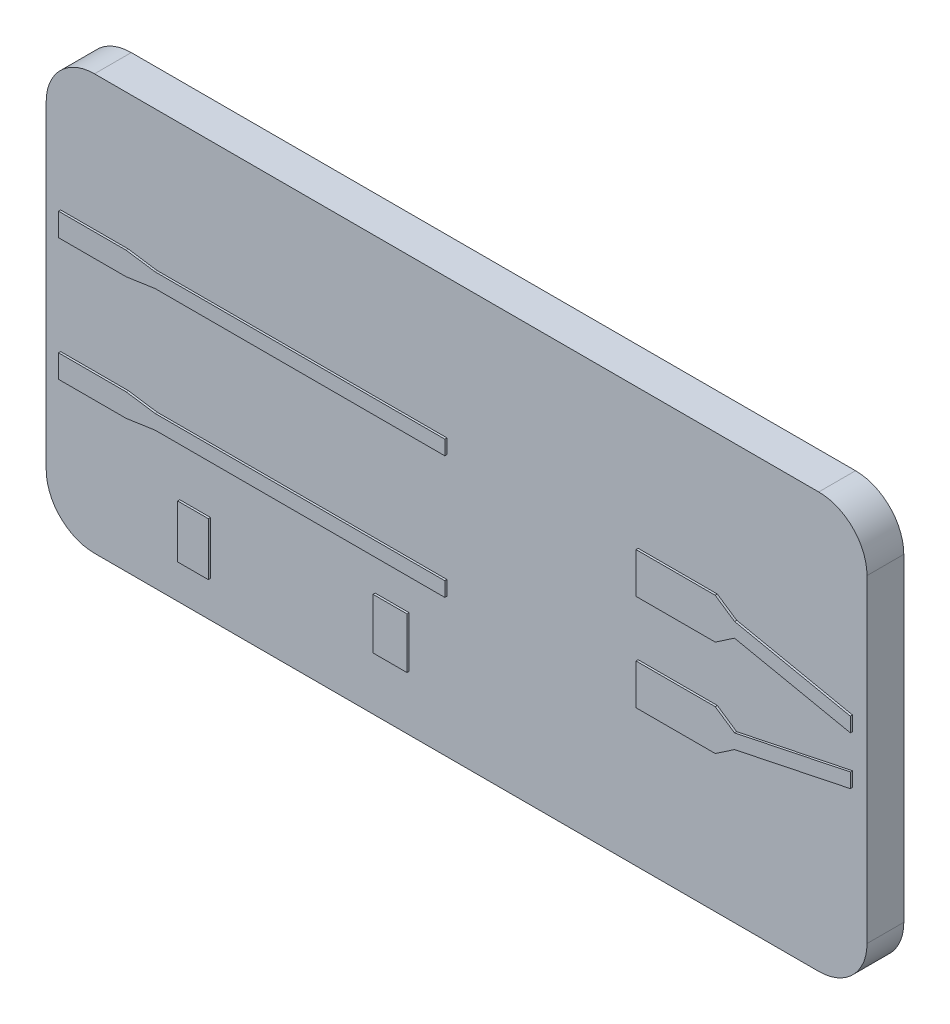
SolidWorks part; units mm, degrees
ref_plane "PL-01 Front" through (0, 0, 0) normal (0, 0, 1) x (1, 0, 0)
ref_plane "PL-02 Top" through (0, 0, 0) normal (0, 1, 0) x (1, 0, 0)
ref_plane "PL-03 Right" through (0, 0, 0) normal (1, 0, 0) x (0, 0, -1)
sketch "Sketch1" plane through (0, 0, 0) normal (0, 0, 1) x (1, 0, 0)
  line L1 (-8, 2.15) -> (-0.5, 2.15)
  line L2 (-8.5, 1.65) -> (-8.5, -1.65)
  line L3 (-8, -2.15) -> (-0.5, -2.15)
  line L4 (0, 1.65) -> (0, -1.65)
  arc A0 (-8.5, -1.65) -> (-8, -2.15) centre (-8, -1.65) ccw
  arc A1 (-8, 2.15) -> (-8.5, 1.65) centre (-8, 1.65) ccw
  arc A2 (-0.5, 2.15) -> (0, 1.65) centre (-0.5, 1.65) cw
  arc A3 (-0.5, -2.15) -> (0, -1.65) centre (-0.5, -1.65) ccw
  dimension "D1" = 0.5
  dimension "D2" = 4.3
  dimension "D3" = 8.5
extrude "BE-00 Board" add sketch "Sketch1" along normal blind 0.381
sketch "Sketch2" plane through (0, 0, 0.381) normal (0, 0, 1) x (1, 0, 0)
  line L0 (-0.15, -0.1751) -> (-0.15, -0.3249)
  line L1 (-0.15, -0.3249) -> (-1.35, -0.5745)
  line L2 (-1.35, -0.5745) -> (-1.5502, -0.7096)
  line L3 (-1.5502, -0.7096) -> (-2.37, -0.7096)
  line L4 (-2.37, -0.7096) -> (-2.37, -0.2896)
  line L5 (-2.37, -0.2896) -> (-1.5502, -0.2896)
  line L6 (-1.5502, -0.2896) -> (-1.35, -0.4246)
  line L7 (-1.35, -0.4246) -> (-0.15, -0.1751)
  line L8 (-1.35, -0.4246) -> (-1.35, -0.5745) construction
  line L9 (-1.0961, 0) -> (-2.5351, 0) construction
  line L10 (-4.35, -0.56) -> (-7.35, -0.56)
  line L11 (-7.35, -0.56) -> (-7.65, -0.516)
  line L12 (-7.65, -0.516) -> (-8.35, -0.516)
  line L13 (-8.35, -0.516) -> (-8.35, -0.754)
  line L14 (-8.35, -0.754) -> (-7.65, -0.754)
  line L15 (-7.65, -0.754) -> (-7.35, -0.71)
  line L16 (-7.35, -0.71) -> (-4.35, -0.71)
  line L17 (-4.35, -0.71) -> (-4.35, -0.56)
  line L19 (-8.5, 1.65) -> (-8.5, -1.65) construction
  line L20 (-4.35, 0.71) -> (-4.35, 0.56)
  line L21 (-7.35, 0.71) -> (-4.35, 0.71)
  line L22 (-7.65, 0.754) -> (-7.35, 0.71)
  line L23 (-8.35, 0.754) -> (-7.65, 0.754)
  line L24 (-8.35, 0.516) -> (-8.35, 0.754)
  line L25 (-7.65, 0.516) -> (-8.35, 0.516)
  line L26 (-7.35, 0.56) -> (-7.65, 0.516)
  line L27 (-4.35, 0.56) -> (-7.35, 0.56)
  line L28 (-1.35, 0.4246) -> (-0.15, 0.1751)
  line L29 (-1.5502, 0.2896) -> (-1.35, 0.4246)
  line L30 (-2.37, 0.2896) -> (-1.5502, 0.2896)
  line L31 (-2.37, 0.7096) -> (-2.37, 0.2896)
  line L32 (-1.5502, 0.7096) -> (-2.37, 0.7096)
  line L33 (-1.35, 0.5745) -> (-1.5502, 0.7096)
  line L34 (-0.15, 0.3249) -> (-1.35, 0.5745)
  line L35 (-0.15, 0.1751) -> (-0.15, 0.3249)
  line L36 (-7.1169, -1.228) -> (-6.7987, -1.228)
  line L37 (-7.1169, -1.228) -> (-7.1169, -1.775)
  line L38 (-7.1169, -1.775) -> (-6.7987, -1.775)
  line L39 (-6.7987, -1.228) -> (-6.7987, -1.775)
  line L40 (-5.0935, -1.0536) -> (-4.7413, -1.0536)
  line L41 (-5.0935, -1.0536) -> (-5.0935, -1.5796)
  line L42 (-5.0935, -1.5796) -> (-4.7413, -1.5796)
  line L43 (-4.7413, -1.0536) -> (-4.7413, -1.5796)
  point P11 (-1.35, -0.4996)
  point P12 (-2.37, -0.4996)
  point P23 (-8.35, -0.635)
  point P42 (-0.15, -0.25)
  dimension "D1" = 0.3501
  dimension "D2" = 0.1499
  dimension "D3" = 34
  dimension "D4" = 0.5791
  dimension "D5" = 0.15
  dimension "D6" = 1.35
  dimension "D7" = 2.37
  dimension "D8" = 0.635
  dimension "D9" = 0.42
  dimension "D10" = 0.238
  dimension "D11" = 0.15
  dimension "D12" = 0.7
  dimension "D13" = 3
  dimension "D14" = 0.8198
  dimension "D15" = 0.5
  dimension "D16" = 0.15
  dimension "D17" = 0.3
extrude "BE-00 Traces" add sketch "Sketch2" along normal blind 0.022
sketch "Sketch4" plane through (0, 0, 0) normal (0, 0, -1) x (-1, 0, 0)
  line L22 (0.5, -2.05) -> (8, -2.05)
  line L23 (0.1, 1.65) -> (0.1, -1.65)
  line L24 (8, 2.05) -> (0.5, 2.05)
  line L25 (8.4, -1.65) -> (8.4, 1.65)
  line L26 (0.5, -2.05) -> (8, -2.05)
  line L27 (0.1, 1.65) -> (0.1, -1.65)
  line L28 (8, 2.05) -> (0.5, 2.05)
  line L29 (8.4, -1.65) -> (8.4, 1.65)
  arc A20 (0.1, -1.65) -> (0.5, -2.05) centre (0.5, -1.65) ccw
  arc A21 (0.5, 2.05) -> (0.1, 1.65) centre (0.5, 1.65) ccw
  arc A22 (8.4, 1.65) -> (8, 2.05) centre (8, 1.65) ccw
  arc A23 (8, -2.05) -> (8.4, -1.65) centre (8, -1.65) ccw
  arc A24 (0.1, -1.65) -> (0.5, -2.05) centre (0.5, -1.65) ccw
  arc A25 (0.5, 2.05) -> (0.1, 1.65) centre (0.5, 1.65) ccw
  arc A26 (8.4, 1.65) -> (8, 2.05) centre (8, 1.65) ccw
  arc A27 (8, -2.05) -> (8.4, -1.65) centre (8, -1.65) ccw
  dimension "D1" = 0.1
extrude "Boss-Extrude1" add sketch "Sketch4" along normal blind 0.022
